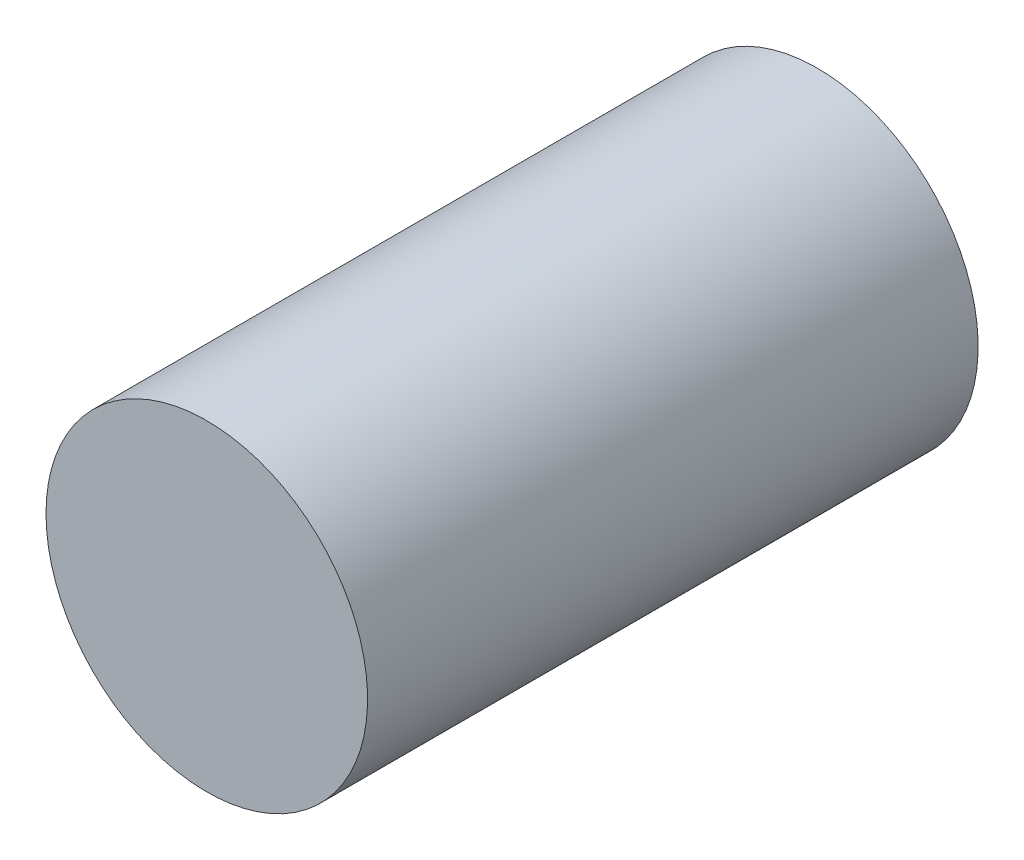
SolidWorks part; units mm, degrees
ref_plane "Front" through (0, 0, 0) normal (0, 0, 1) x (1, 0, 0)
ref_plane "Top" through (0, 0, 0) normal (0, 1, 0) x (1, 0, 0)
ref_plane "Right" through (0, 0, 0) normal (1, 0, 0) x (0, 0, -1)
sketch "Sketch1" plane through (0, 0, 0) normal (0, 0, 1) x (1, 0, 0)
  circle A0 centre (0, 0) radius 40.132
  dimension "D1" = 80.264
extrude "Boss-Extrude1" add sketch "Sketch1" along normal blind 152.4
